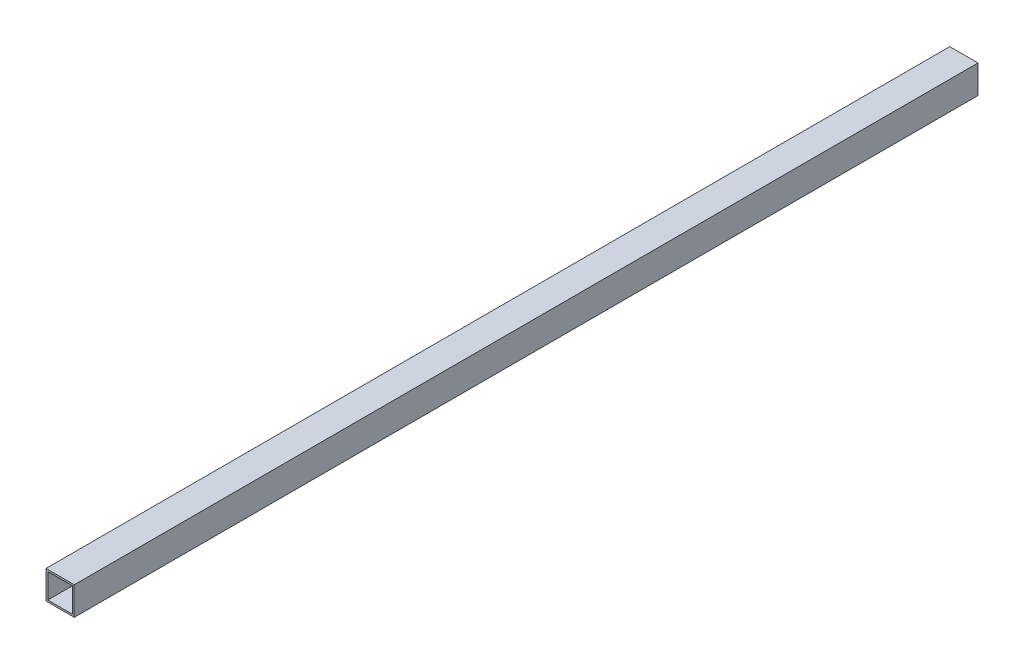
SolidWorks part; units mm, degrees
material "AISI 1020"
ref_plane "Front Plane" through (0, 0, 0) normal (0, 0, 1) x (1, 0, 0)
ref_plane "Top Plane" through (0, 0, 0) normal (0, 1, 0) x (1, 0, 0)
ref_plane "Right Plane" through (0, 0, 0) normal (1, 0, 0) x (0, 0, -1)
sketch "Sketch1" plane through (0, 0, 0) normal (0, 0, 1) x (1, 0, 0)
  line L0 (22.225, 22.225) -> (22.225, 25.4) construction
  line L1 (-25.4, -25.4) -> (25.4, -25.4)
  line L2 (-25.4, -25.4) -> (-25.4, 25.4)
  line L3 (-25.4, 25.4) -> (25.4, 25.4)
  line L4 (25.4, -25.4) -> (25.4, 25.4)
  line L5 (-25.4, -25.4) -> (25.4, 25.4) construction
  line L6 (-25.4, 25.4) -> (25.4, -25.4) construction
  line L7 (-22.225, -22.225) -> (22.225, -22.225)
  line L8 (-22.225, -22.225) -> (-22.225, 22.225)
  line L9 (-22.225, 22.225) -> (22.225, 22.225)
  line L10 (22.225, -22.225) -> (22.225, 22.225)
  line L11 (-22.225, -22.225) -> (22.225, 22.225) construction
  line L12 (-22.225, 22.225) -> (22.225, -22.225) construction
  line L13 (22.225, -22.225) -> (25.4, -22.225) construction
  point P0 (0, 0)
  point P6 (0, 0)
  dimension "D2" = 50.8
  dimension "D3" = 3.175
extrude "Boss-Extrude1" add sketch "Sketch1" along normal blind 1625.6
